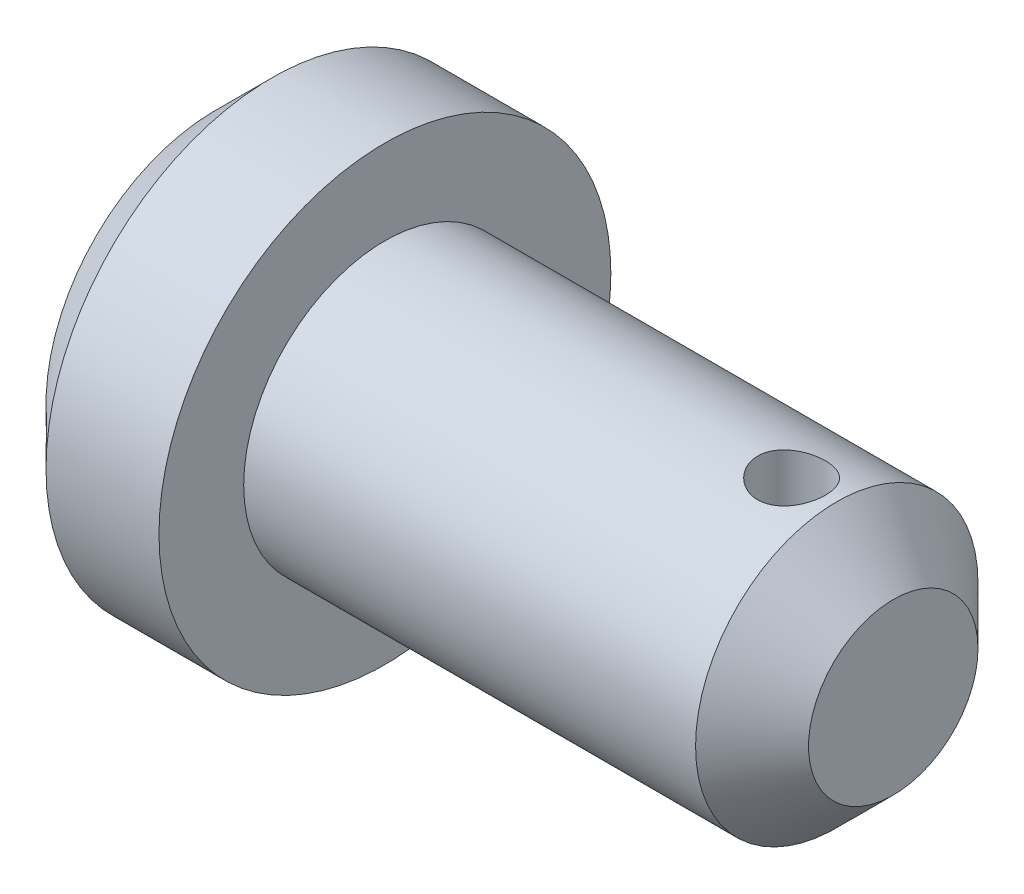
SolidWorks part; units mm, degrees
ref_plane "Front Plane" through (0, 0, 0) normal (0, 0, 1) x (1, 0, 0)
ref_plane "Top Plane" through (0, 0, 0) normal (0, 1, 0) x (1, 0, 0)
ref_plane "Right Plane" through (0, 0, 0) normal (1, 0, 0) x (0, 0, -1)
sketch "Sketch1" plane through (0, 0, 0) normal (1, 0, 0) x (0, 0, -1)
  circle A0 centre (0, 0) radius 40
  dimension "D1" = 80
extrude "Boss-Extrude1" add sketch "Sketch1" along normal blind 30
chamfer "Chamfer1" distance 10 angle 45 1 edges at (0, 0, -40)
ref_plane "Plane1" through (30, 0, 0) normal (1, 0, 0) x (0, 0, -1)
sketch "Sketch2" plane through (30, 0, 0) normal (1, 0, 0) x (0, 0, -1)
  circle A0 centre (0, 0) radius 25
  dimension "D1" = 50
extrude "Boss-Extrude2" add sketch "Sketch2" along normal blind 90
chamfer "Chamfer2" distance 10 angle 45 1 edges at (120, 0, -25)
ref_plane "Plane2" through (0, 25, 0) normal (0, 1, 0) x (1, 0, 0)
sketch "Sketch3" plane through (0, 25, 0) normal (0, 1, 0) x (1, 0, 0)
  line L1 (30, -44) -> (30, 44) construction
  circle A0 centre (102, 0) radius 6
  point P2 (93.6285, 0)
  point P4 (94.0367, -1.8292)
  dimension "D1" = 12
  dimension "D2" = 72
extrude "Cut-Extrude1" cut sketch "Sketch3" against normal blind 90
